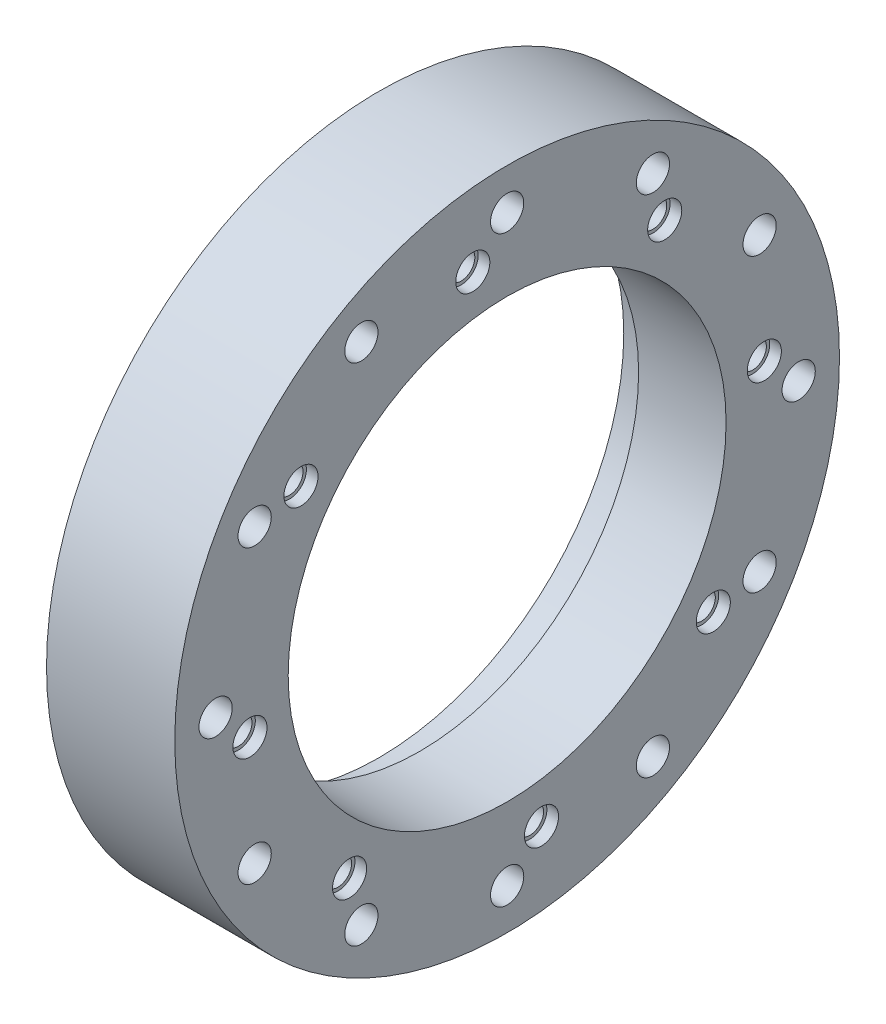
SolidWorks part; units mm, degrees
material "PLA"
ref_plane "Front Plane" through (0, 0, 0) normal (0, 0, 1) x (1, 0, 0)
ref_plane "Top Plane" through (0, 0, 0) normal (0, 1, 0) x (1, 0, 0)
ref_plane "Right Plane" through (0, 0, 0) normal (1, 0, 0) x (0, 0, -1)
sketch "Sketch1" plane through (0, 0, 0) normal (1, 0, 0) x (0, 0, -1)
  circle A0 centre (0, 0) radius 45.72
  circle A1 centre (0, 0) radius 57
  dimension "D1" = 91.44
  dimension "D2" = 114
extrude "Boss-Extrude1" add sketch "Sketch1" along normal blind 15 contours A0
sketch "Sketch2" plane through (15, 0, 0) normal (1, 0, 0) x (0, 0, -1)
  circle A0 centre (0, 0) radius 35.5
  circle A1 centre (0, 0) radius 45.72
  circle A2 centre (0, 0) radius 45.72 construction
  dimension "D1" = 71
sketch "Sketch3" plane through (0, 0, 0) normal (-1, 0, 0) x (0, 0, 1)
  circle A0 centre (0, 0) radius 37.55
  circle A1 centre (0, 0) radius 49.0018
  dimension "D1" = 75.1
extrude "Boss-Extrude3" add sketch "Sketch3" against normal up to surface (15 mm away) up to face at (15, 0, -57)
sketch "Sketch4" plane through (15, 0, 0) normal (1, 0, 0) x (0, 0, -1)
  circle A0 centre (0, 50) radius 2
  dimension "D1" = 4
  dimension "D2" = 50
extrude "Cut-Extrude1" cut sketch "Sketch4" against normal up to next
sketch "Sketch6" plane through (15, 0, 0) normal (1, 0, 0) x (0, 0, -1)
  line L0 (-5.8918, 44.1082) -> (0, 50)
  line L1 (0, 50) -> (0, 0) construction
  circle A0 centre (-5.8918, 44.1082) radius 1.5
  circle A1 centre (0, 0) radius 37.55 construction
  dimension "D1" = 3
  dimension "D2" = 44.5
  dimension "D3" = 45
extrude "Cut-Extrude2" cut sketch "Sketch6" against normal through all contours A0
pattern_circular "CirPattern2" count 8 over 360 about axis through (0, 0, 0) along (1, 0, 0) of "Cut-Extrude2"
pattern_circular "CirPattern1" count 12 over 360 about axis through (0, 0, 0) along (1, 0, 0) of "Cut-Extrude1"
sketch "Sketch7" plane through (15, 0, 0) normal (1, 0, 0) x (0, 0, -1)
  line L7 (-43.3013, 25) -> (-38.9711, 22.5) construction
  line L8 (0, 0) -> (-38.9711, 22.5) construction
  line L9 (-39.2598, 25) -> (-41.2805, 28.5)
  line L10 (-41.2805, 28.5) -> (-45.322, 28.5)
  line L11 (-45.322, 28.5) -> (-47.3427, 25)
  line L12 (-47.3427, 25) -> (-45.322, 21.5)
  line L13 (-45.322, 21.5) -> (-41.2805, 21.5)
  line L14 (-41.2805, 21.5) -> (-39.2598, 25)
  circle A0 centre (-43.3013, 25) radius 3.5 construction
  circle A1 centre (-43.3013, 25) radius 3.5 construction
  dimension "D1" = 45
  dimension "D2" = 7
sketch "Sketch10" plane through (0, 0, 0) normal (-1, 0, 0) x (0, 0, 1)
  circle A0 centre (0, 0) radius 42
  circle A1 centre (-25, 43.3013) radius 2 construction
  circle A2 centre (0, 0) radius 57
  circle A3 centre (0, 0) radius 57 construction
  circle A6 centre (-27.0231, 35.3553) radius 1.5 construction
  circle A8 centre (5.8918, 44.1082) radius 1.5 construction
  circle A10 centre (35.3553, 27.0231) radius 1.5 construction
  circle A13 centre (44.1082, -5.8918) radius 1.5 construction
  circle A15 centre (27.0231, -35.3553) radius 1.5 construction
  circle A18 centre (-44.1082, 5.8918) radius 1.5 construction
  circle A21 centre (-35.3553, -27.0231) radius 1.5 construction
  circle A23 centre (-5.8918, -44.1082) radius 1.5 construction
  circle A26 centre (-27.0231, 35.3553) radius 1.5
  circle A28 centre (5.8918, 44.1082) radius 1.5
  circle A30 centre (35.3553, 27.0231) radius 1.5
  circle A33 centre (44.1082, -5.8918) radius 1.5
  circle A35 centre (27.0231, -35.3553) radius 1.5
  circle A38 centre (-44.1082, 5.8918) radius 1.5
  circle A41 centre (-35.3553, -27.0231) radius 1.5
  circle A43 centre (-5.8918, -44.1082) radius 1.5
  circle A44 centre (0, 50) radius 2 construction
  circle A45 centre (25, 43.3013) radius 2 construction
  circle A46 centre (43.3013, 25) radius 2 construction
  circle A47 centre (50, 0) radius 2 construction
  circle A48 centre (43.3013, -25) radius 2 construction
  circle A49 centre (25, -43.3013) radius 2 construction
  circle A50 centre (0, -50) radius 2 construction
  circle A51 centre (-25, -43.3013) radius 2 construction
  circle A52 centre (-43.3013, -25) radius 2 construction
  circle A53 centre (-50, 0) radius 2 construction
  circle A54 centre (-43.3013, 25) radius 2 construction
  circle A55 centre (-25, 43.3013) radius 2
  circle A56 centre (0, 50) radius 2
  circle A57 centre (25, 43.3013) radius 2
  circle A58 centre (43.3013, 25) radius 2
  circle A59 centre (50, 0) radius 2
  circle A60 centre (43.3013, -25) radius 2
  circle A61 centre (25, -43.3013) radius 2
  circle A62 centre (0, -50) radius 2
  circle A63 centre (-25, -43.3013) radius 2
  circle A64 centre (-43.3013, -25) radius 2
  circle A65 centre (-50, 0) radius 2
  circle A66 centre (-43.3013, 25) radius 2
  dimension "D1" = 15
extrude "Boss-Extrude4" add sketch "Sketch10" along normal blind 7
sketch "Sketch11" plane through (15, 0, 0) normal (1, 0, 0) x (0, 0, -1)
  circle A0 centre (-5.8918, 44.1082) radius 2.5
  dimension "D1" = 5
ref_plane "Plane1" through (7.5, 0, 0) normal (1, 0, 0) x (0, 0, -1)
sketch "Sketch12" plane through (15, 0, 0) normal (1, 0, 0) x (0, 0, -1)
  circle A0 centre (-35.3553, 27.0231) radius 2.35
  circle A1 centre (-35.3553, 27.0231) radius 1.5 construction
  circle A9 centre (-5.8918, 44.1082) radius 2.35
  circle A10 centre (27.0231, 35.3553) radius 2.35
  circle A11 centre (44.1082, 5.8918) radius 2.35
  circle A12 centre (35.3553, -27.0231) radius 2.35
  circle A13 centre (5.8918, -44.1082) radius 2.35
  circle A14 centre (-27.0231, -35.3553) radius 2.35
  circle A15 centre (-44.1082, -5.8918) radius 2.35
  point P20 (0, 0)
  dimension "D1" = 4.7
  dimension "D2" = 8
extrude "Cut-Extrude3" cut sketch "Sketch12" against normal blind 6.5
sketch "Sketch13" plane through (15, 0, 0) normal (1, 0, 0) x (0, 0, -1)
  circle A0 centre (-35.3553, 27.0231) radius 2.925
  circle A8 centre (-5.8918, 44.1082) radius 2.925
  circle A9 centre (27.0231, 35.3553) radius 2.925
  circle A10 centre (44.1082, 5.8918) radius 2.925
  circle A11 centre (35.3553, -27.0231) radius 2.925
  circle A12 centre (5.8918, -44.1082) radius 2.925
  circle A13 centre (-27.0231, -35.3553) radius 2.925
  circle A14 centre (-44.1082, -5.8918) radius 2.925
  point P19 (0, 0)
  dimension "D1" = 5.85
  dimension "D2" = 8
extrude "Cut-Extrude4" cut sketch "Sketch13" against normal blind 2
sketch "Sketch14" plane through (15, 0, 0) normal (1, 0, 0) x (0, 0, -1)
  circle A0 centre (-43.3013, 25) radius 2.85
  circle A1 centre (-25, 43.3013) radius 2.85
  circle A2 centre (0, 50) radius 2.85
  circle A3 centre (25, 43.3013) radius 2.85
  circle A4 centre (43.3013, 25) radius 2.85
  circle A5 centre (50, 0) radius 2.85
  circle A6 centre (43.3013, -25) radius 2.85
  circle A7 centre (25, -43.3013) radius 2.85
  circle A8 centre (0, -50) radius 2.85
  circle A9 centre (-25, -43.3013) radius 2.85
  circle A10 centre (-43.3013, -25) radius 2.85
  circle A11 centre (-50, 0) radius 2.85
  point P27 (0, 0)
  dimension "D1" = 5.7
  dimension "D2" = 12
extrude "Cut-Extrude5" cut sketch "Sketch14" against normal blind 9
